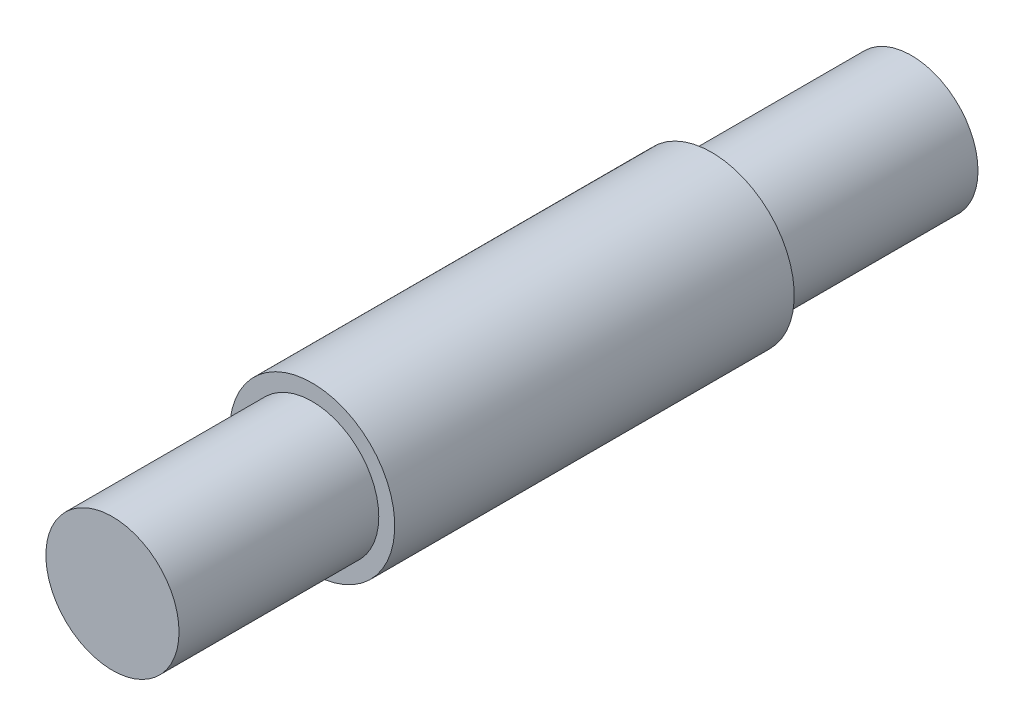
SolidWorks part; units mm, degrees
ref_plane "Front Plane" through (0, 0, 0) normal (0, 0, 1) x (1, 0, 0)
ref_plane "Top Plane" through (0, 0, 0) normal (0, 1, 0) x (1, 0, 0)
ref_plane "Right Plane" through (0, 0, 0) normal (1, 0, 0) x (0, 0, -1)
sketch "Sketch1" plane through (0, 0, 0) normal (0, 0, 1) x (1, 0, 0)
  circle A0 centre (0, 0) radius 3.937
  dimension "D1" = 7.874
extrude "Boss-Extrude2" add sketch "Sketch1" along normal blind 19.05
sketch "Sketch3" plane through (0, 0, 19.05) normal (0, 0, 1) x (1, 0, 0)
  circle A0 centre (0, 0) radius 3.175
  dimension "D1" = 6.35
extrude "Boss-Extrude3" add sketch "Sketch3" along normal blind 9.525 and the other way blind 28.575
